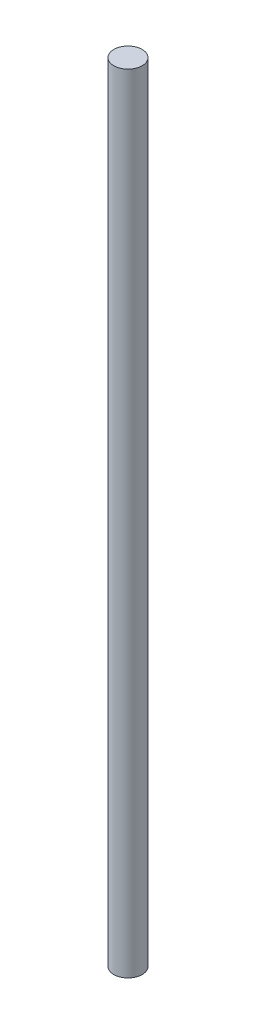
SolidWorks part; units mm, degrees
ref_plane "前视基准面" through (0, 0, 0) normal (0, 0, 1) x (1, 0, 0)
ref_plane "上视基准面" through (0, 0, 0) normal (0, 1, 0) x (1, 0, 0)
ref_plane "右视基准面" through (0, 0, 0) normal (1, 0, 0) x (0, 0, -1)
other "Configuration Table"
sketch "草图1" plane through (0, 0, 0) normal (0, 1, 0) x (1, 0, 0)
  circle A0 centre (0, 0) radius 3.6
  dimension "D1" = 7.2
extrude "凸台-拉伸2" add sketch "草图1" along normal blind 200
